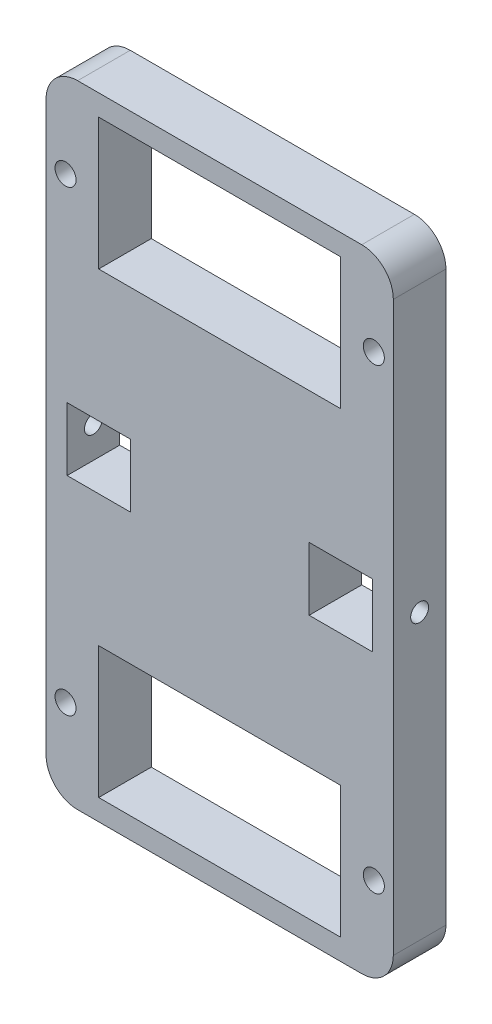
SolidWorks part; units mm, degrees
ref_plane "Front Plane" through (0, 0, 0) normal (0, 0, 1) x (1, 0, 0)
ref_plane "Top Plane" through (0, 0, 0) normal (0, 1, 0) x (1, 0, 0)
ref_plane "Right Plane" through (0, 0, 0) normal (1, 0, 0) x (0, 0, -1)
sketch "Sketch1" plane through (0, 0, 0) normal (0, 0, 1) x (1, 0, 0)
  line L0 (0, 30) -> (0, -30) construction
  line L1 (-16.5, -30) -> (16.5, -30)
  line L2 (-16.5, -30) -> (-16.5, 30)
  line L3 (-16.5, 30) -> (16.5, 30)
  line L4 (16.5, -30) -> (16.5, 30)
  line L5 (-16.5, -30) -> (16.5, 30) construction
  line L6 (-16.5, 30) -> (16.5, -30) construction
  line L7 (-16.5, 0) -> (16.5, 0) construction
  line L8 (-11.5, 28) -> (11.5, 28)
  line L9 (-11.5, 28) -> (-11.5, 15.5)
  line L10 (-11.5, 15.5) -> (11.5, 15.5)
  line L11 (11.5, 28) -> (11.5, 15.5)
  line L12 (-11.5, 28) -> (11.5, 15.5) construction
  line L13 (-11.5, 15.5) -> (11.5, 28) construction
  line L14 (-11.5, -15.5) -> (11.5, -15.5)
  line L15 (11.5, -28) -> (11.5, -15.5)
  line L16 (-11.5, -28) -> (11.5, -28)
  line L17 (-11.5, -28) -> (-11.5, -15.5)
  line L18 (-16.5, 21.75) -> (16.5, 21.75) construction
  line L19 (14.5, 3) -> (8.5, 3)
  line L20 (-14.5, -3) -> (-8.5, -3)
  line L21 (-14.5, -3) -> (-14.5, 3)
  line L22 (-14.5, 3) -> (-8.5, 3)
  line L23 (-8.5, -3) -> (-8.5, 3)
  line L24 (-14.5, -3) -> (-8.5, 3) construction
  line L25 (-14.5, 3) -> (-8.5, -3) construction
  line L26 (8.5, -3) -> (8.5, 3)
  line L27 (14.5, -3) -> (8.5, -3)
  line L28 (14.5, -3) -> (14.5, 3)
  circle A0 centre (-14.65, 21.75) radius 1
  circle A1 centre (14.65, 21.75) radius 1
  circle A2 centre (14.65, -21.75) radius 1
  circle A3 centre (-14.65, -21.75) radius 1
  point P0 (0, 0)
  point P8 (0, 21.75)
  point P29 (-11.5, 0)
  dimension "D6" = 2
  dimension "D7" = 1.85
  dimension "D1" = 60
  dimension "D2" = 33
  dimension "D3" = 12.5
  dimension "D4" = 23
  dimension "D5" = 2
  dimension "D8" = 6
  dimension "D9" = 6
  dimension "D10" = 2
extrude "Boss-Extrude1" add sketch "Sketch1" along normal blind 5
sketch "Sketch2" plane through (16.5, 0, 0) normal (1, 0, 0) x (0, 0, -1)
  line L0 (-2.5, 30) -> (-2.5, -30) construction
  line L1 (-5, 30) -> (0, 30) construction
  line L2 (-5, -30) -> (0, -30) construction
  line L3 (0, 0) -> (-5, 0) construction
  line L4 (-5, -30) -> (-5, 30) construction
  circle A0 centre (-2.5, 0) radius 0.85
  dimension "D1" = 1.7
extrude "Cut-Extrude1" cut sketch "Sketch2" against normal blind 3
sketch "Sketch3" plane through (-16.5, 0, 0) normal (-1, 0, 0) x (0, 0, 1)
  line L0 (2.5, 30) -> (2.5, -30) construction
  line L1 (5, 30) -> (0, 30) construction
  line L2 (5, -30) -> (0, -30) construction
  line L3 (0, 0) -> (5, 0) construction
  line L4 (0, 30) -> (0, -30) construction
  line L5 (5, 30) -> (5, -30) construction
  circle A0 centre (2.5, 0) radius 0.85
  dimension "D1" = 1.7
extrude "Cut-Extrude2" cut sketch "Sketch3" against normal blind 3
fillet "Fillet1" radius 3 4 edges at (16.5, -30, 2.5) (16.5, 30, 2.5) (-16.5, 30, 2.5) (-16.5, -30, 2.5)
